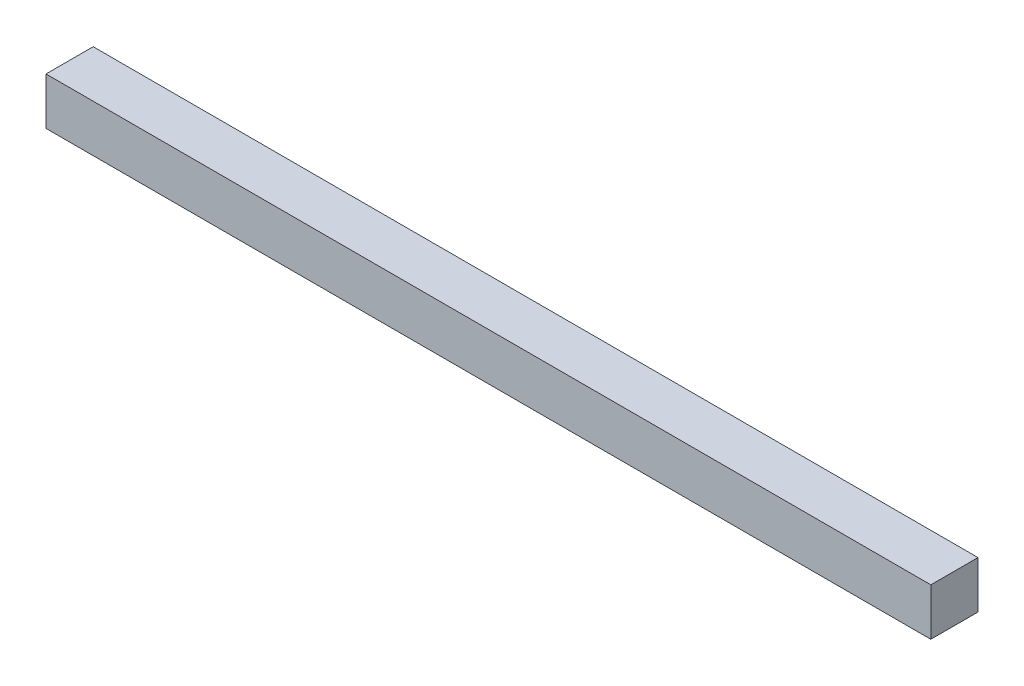
SolidWorks part; units mm, degrees
ref_plane "Front Plane" through (0, 0, 0) normal (0, 0, 1) x (1, 0, 0)
ref_plane "Top Plane" through (0, 0, 0) normal (0, 1, 0) x (1, 0, 0)
ref_plane "Right Plane" through (0, 0, 0) normal (1, 0, 0) x (0, 0, -1)
sketch "Sketch1" plane through (0, 0, 0) normal (0, 1, 0) x (1, 0, 0)
  line L1 (0, 0) -> (75, 0)
  line L2 (0, 0) -> (0, -4)
  line L3 (0, -4) -> (75, -4)
  line L4 (75, 0) -> (75, -4)
  line L5 (0, 0) -> (75, -4) construction
  line L6 (0, -4) -> (75, 0) construction
  point P4 (37.5, -2)
  dimension "D1" = 4
  dimension "D2" = 75
extrude "Boss-Extrude1" add sketch "Sketch1" along normal blind 4
